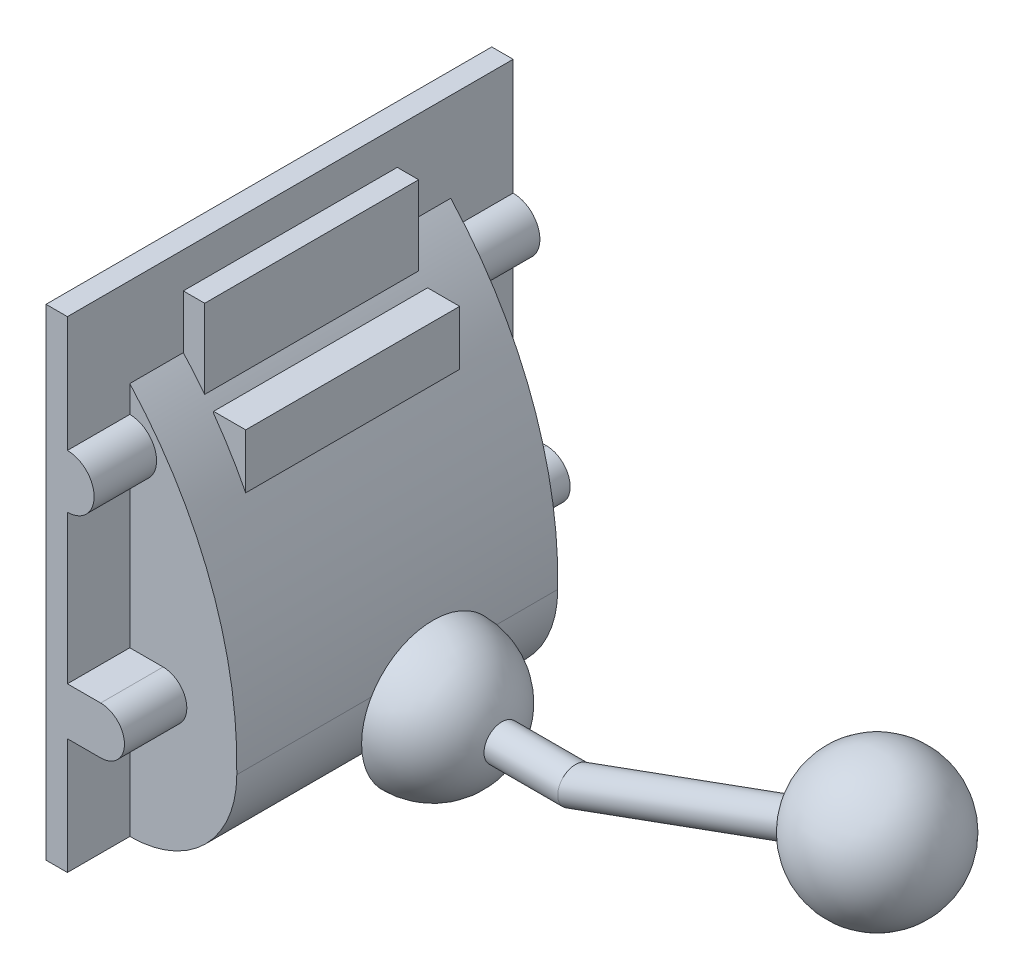
SolidWorks part; units mm, degrees
ref_plane "Front Plane" through (0, 0, 0) normal (0, 0, 1) x (1, 0, 0)
ref_plane "Top Plane" through (0, 0, 0) normal (0, 1, 0) x (1, 0, 0)
ref_plane "Right Plane" through (0, 0, 0) normal (1, 0, 0) x (0, 0, -1)
sketch "Sketch1" plane through (0, 0, 0) normal (0, 0, 1) x (1, 0, 0)
  line L0 (0, 0) -> (0, 330)
  arc A0 (0, 0) -> (90, 90) centre (0, 90) ccw
  arc A1 (90, 90) -> (0, 330) centre (-254.9178, 97.5308) ccw
  dimension "D1" = 330
  dimension "D2" = 90
  dimension "D3" = 345
extrude "Boss-Extrude1" add sketch "Sketch1" along normal mid plane 270 contours A1 L0 A0
sketch "Sketch2" plane through (0, 0, 0) normal (-1, 0, 0) x (0, 0, 1)
  line L1 (-187.5, 0) -> (187.5, 0)
  line L2 (-187.5, 0) -> (-187.5, 405)
  line L3 (-187.5, 405) -> (187.5, 405)
  line L4 (187.5, 0) -> (187.5, 405)
  point P4 (0, 0)
  dimension "D1" = 375
  dimension "D2" = 405
extrude "Boss-Extrude2" add sketch "Sketch2" along normal blind 18
sketch "Sketch3" plane through (0, 0, 0) normal (0, 0, 1) x (1, 0, 0)
  line L0 (0, 0) -> (0, 405) construction
  line L1 (0, 375) -> (18, 375)
  line L2 (0, 375) -> (0, 269.387)
  line L3 (0, 269.387) -> (18, 269.387)
  line L4 (18, 375) -> (18, 269.387)
  line L6 (52.5, 300) -> (25.5, 300)
  line L7 (52.5, 300) -> (52.5, 169.8612)
  line L8 (52.5, 169.8612) -> (25.5, 169.8612)
  line L9 (25.5, 300) -> (25.5, 169.8612)
  dimension "D1" = 18
  dimension "D2" = 27
  dimension "D3" = 45
  dimension "D4" = 52.5
  dimension "D5" = 75
extrude "Boss-Extrude3" add sketch "Sketch3" along normal mid plane 180
sketch "Sketch4" plane through (0, 0, 187.5) normal (0, 0, 1) x (1, 0, 0)
  line L0 (0, 0) -> (0, 405) construction
  line L1 (0, 97.5) -> (27.9823, 97.5)
  line L2 (0, 97.5) -> (0, 137.5)
  line L3 (0, 137.5) -> (27.9823, 137.5)
  line L4 (0, 375) -> (0, 330) construction
  line L5 (0, 0) -> (0, 330) construction
  line L6 (0, 307.5) -> (0, 262.5)
  arc A0 (27.9823, 97.5) -> (27.9823, 137.5) centre (27.9823, 117.5) ccw
  arc A1 (0, 307.5) -> (0, 262.5) centre (0, 285) cw
  dimension "D3" = 22.5
  dimension "D1" = 97.5
  dimension "D2" = 40
  dimension "D4" = 90
extrude "Boss-Extrude4" add sketch "Sketch4" against normal up to surface (375 mm away) up to face at (-9, 202.5, -187.5)
sketch "Sketch5" plane through (0, 0, 0) normal (1, 0, 0) x (0, 0, -1)
  line L0 (-135, 90) -> (135, 90) construction
  circle A0 centre (0, 90) radius 15
  dimension "D1" = 30
extrude "Boss-Extrude5" add sketch "Sketch5" along normal blind 240
ref_plane "Plane1" through (0, 90, 0) normal (0, -1, 0) x (-1, 0, 0)
sketch "Sketch6" plane through (0, 90, 0) normal (0, -1, 0) x (-1, 0, 0)
  line L0 (-120, 0) -> (-120, -60)
  line L1 (-120, 0) -> (-180, 0)
  line L2 (-240, 15) -> (-240, -15) construction
  arc A0 (-180, 0) -> (-120, -60) centre (-120, 0) ccw
  dimension "D1" = 60
  dimension "D2" = 120
revolve "Revolve1" add sketch "Sketch6" angle 360 about L1
sketch "Sketch7" plane through (0, 0, 0) normal (0, 0, 1) x (1, 0, 0)
  line L0 (240, 90) -> (493.717, 182.3454)
  line L1 (240, 75) -> (240, 105) construction
  line L2 (88.7412, 75) -> (240, 75) construction
  dimension "D1" = 270
  dimension "D2" = 20
sketch "Sketch8" plane through (240, 0, 0) normal (1, 0, 0) x (0, 0, -1)
  circle A1 centre (0, 90) radius 15
  circle A2 centre (0, 90) radius 15
  dimension "D1" = 0
sweep "Sweep1" add profiles "Sketch8" path "Sketch7"
sketch "Sketch9" plane through (0, 0, 0) normal (0, 0, 1) x (1, 0, 0)
  line L0 (493.717, 122.3454) -> (493.717, 242.3454)
  line L2 (493.717, 167.3454) -> (493.717, 197.3454) construction
  arc A0 (493.717, 122.3454) -> (493.717, 242.3454) centre (493.717, 182.3454) ccw
  point P5 (493.717, 182.3454)
  dimension "D1" = 120
revolve "Revolve2" add sketch "Sketch9" angle 360 about L0
